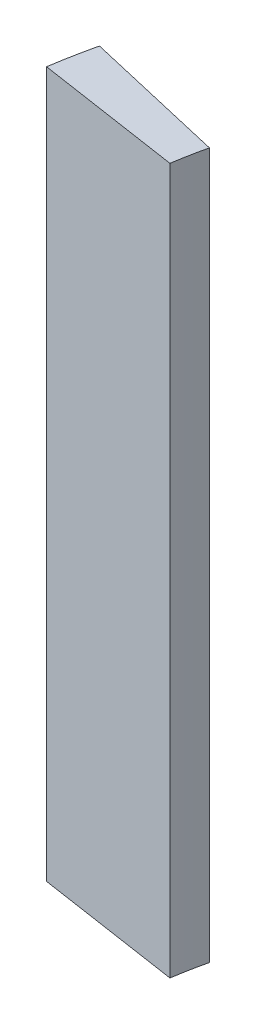
SolidWorks part; units mm, degrees
material "PTFE (general)"
ref_plane "Front Plane" through (0, 0, 0) normal (0, 0, 1) x (1, 0, 0)
ref_plane "Top Plane" through (0, 0, 0) normal (0, 1, 0) x (1, 0, 0)
ref_plane "Right Plane" through (0, 0, 0) normal (1, 0, 0) x (0, 0, -1)
sketch "Sketch1" plane through (0, 0, 0) normal (0, 1, 0) x (1, 0, 0)
  line L0 (-5.1524, -0.729) -> (4.7354, -2.223)
  line L1 (-4.5741, 2.294) -> (-4.6028, 2.2995)
  line L2 (5.167, 0.0334) -> (-4.6028, 2.2995) construction
  line L3 (-4.5741, 2.294) -> (5.167, 0.0334)
  arc A2 (5.167, 0.0334) -> (4.7354, -2.223) centre (33.9255, -6.637) ccw
  arc A3 (-4.5741, 2.294) -> (-5.1524, -0.729) centre (33.9255, -6.637) ccw
  dimension "D1" = 29.522
  dimension "D2" = 39.522
extrude "Boss-Extrude1" add sketch "Sketch1" along normal blind 48
